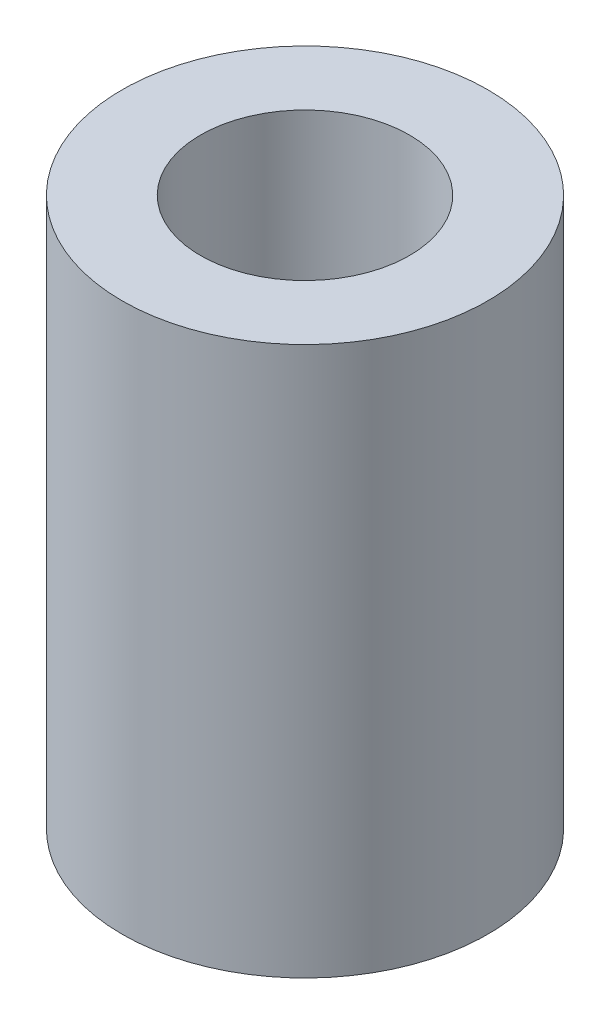
SolidWorks part; units mm, degrees
material "PLA"
ref_plane "Front Plane" through (0, 0, 0) normal (0, 0, 1) x (1, 0, 0)
ref_plane "Top Plane" through (0, 0, 0) normal (0, 1, 0) x (1, 0, 0)
ref_plane "Right Plane" through (0, 0, 0) normal (1, 0, 0) x (0, 0, -1)
ref_plane "Plane1" through (0, 0, 0) normal (0, 1, 0) x (1, 0, 0)
sketch "Sketch1" plane through (0, 0, 0) normal (0, 1, 0) x (1, 0, 0)
  circle A0 centre (0, 0) radius 3.5
  circle A1 centre (0, 0) radius 2
  dimension "D1" = 4
  dimension "D2" = 7
extrude "Boss-Extrude1" add sketch "Sketch1" along normal blind 10.5
